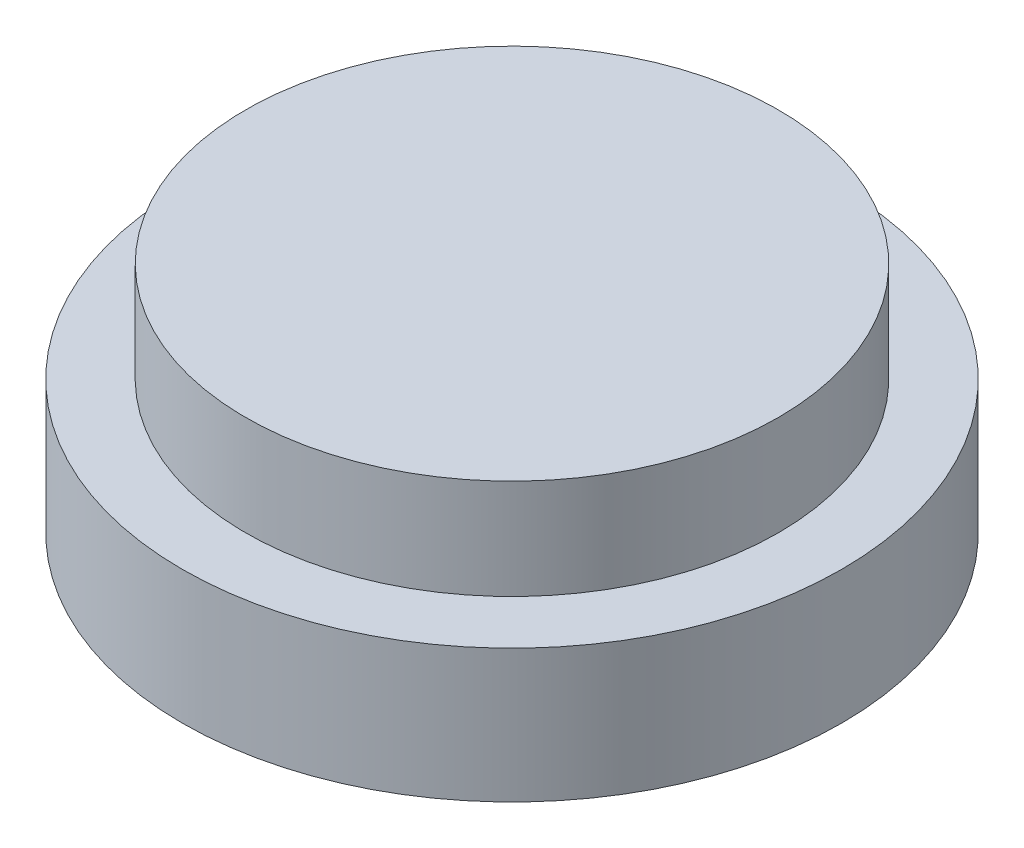
SolidWorks part; units mm, degrees
material "Cast Stainless Steel"
ref_plane "Front Plane" through (0, 0, 0) normal (0, 0, 1) x (1, 0, 0)
ref_plane "Top Plane" through (0, 0, 0) normal (0, 1, 0) x (1, 0, 0)
ref_plane "Right Plane" through (0, 0, 0) normal (1, 0, 0) x (0, 0, -1)
sketch "Sketch1" plane through (0, 0, 0) normal (0, 0, 1) x (1, 0, 0)
  line L0 (0, 0) -> (0, 63.5)
  line L1 (0, 63.5) -> (101.6, 63.5)
  line L2 (101.6, 63.5) -> (101.6, 25.4)
  line L3 (101.6, 25.4) -> (125.73, 25.4)
  line L4 (125.73, 25.4) -> (125.73, -25.4)
  line L5 (125.73, -25.4) -> (78.74, -25.4)
  line L6 (78.74, -25.4) -> (78.74, 0)
  line L7 (78.74, 0) -> (0, 0)
  dimension "D1" = 88.9
  dimension "D2" = 25.4
  dimension "D3" = 78.74
  dimension "D4" = 125.73
  dimension "D5" = 101.6
  dimension "D6" = 50.8
revolve "Revolve1" add sketch "Sketch1" angle 360 about L0
